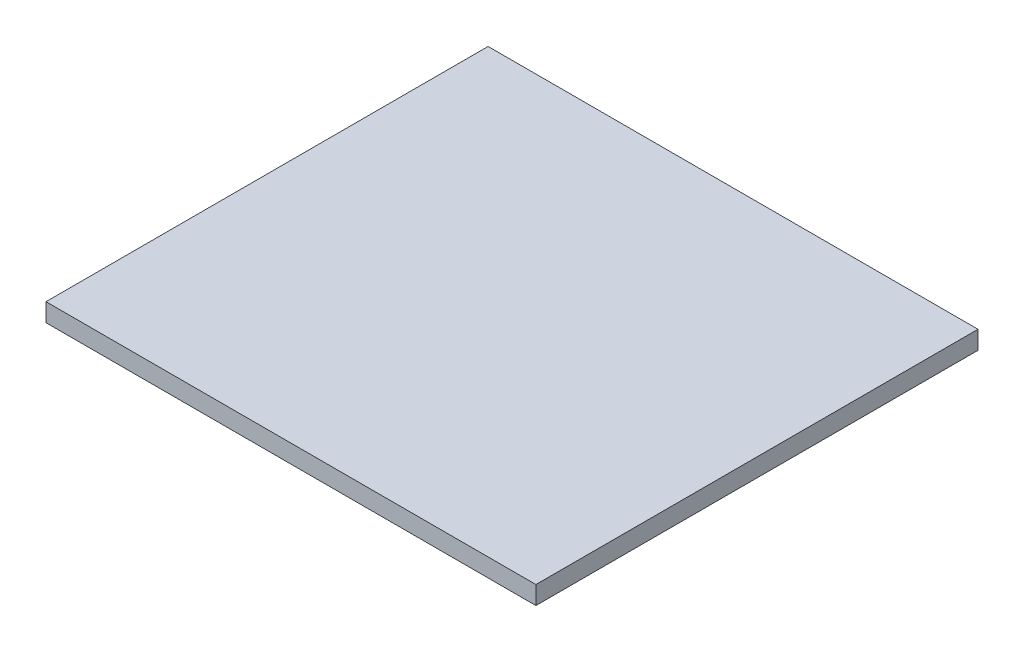
SolidWorks part; units mm, degrees
ref_plane "Front Plane" through (0, 0, 0) normal (0, 0, 1) x (1, 0, 0)
ref_plane "Top Plane" through (0, 0, 0) normal (0, 1, 0) x (1, 0, 0)
ref_plane "Right Plane" through (0, 0, 0) normal (1, 0, 0) x (0, 0, -1)
sketch "Sketch1" plane through (0, 0, 0) normal (0, 1, 0) x (1, 0, 0)
  line L1 (9, 0) -> (91, 0)
  line L2 (9, 0) -> (9, 74)
  line L3 (9, 74) -> (91, 74)
  line L4 (91, 0) -> (91, 74)
extrude "Boss-Extrude1" add sketch "Sketch1" along normal blind 3.05
ref_plane "center-of-module" through (50, 0, 0) normal (1, 0, 0) x (0, 0, -1)
